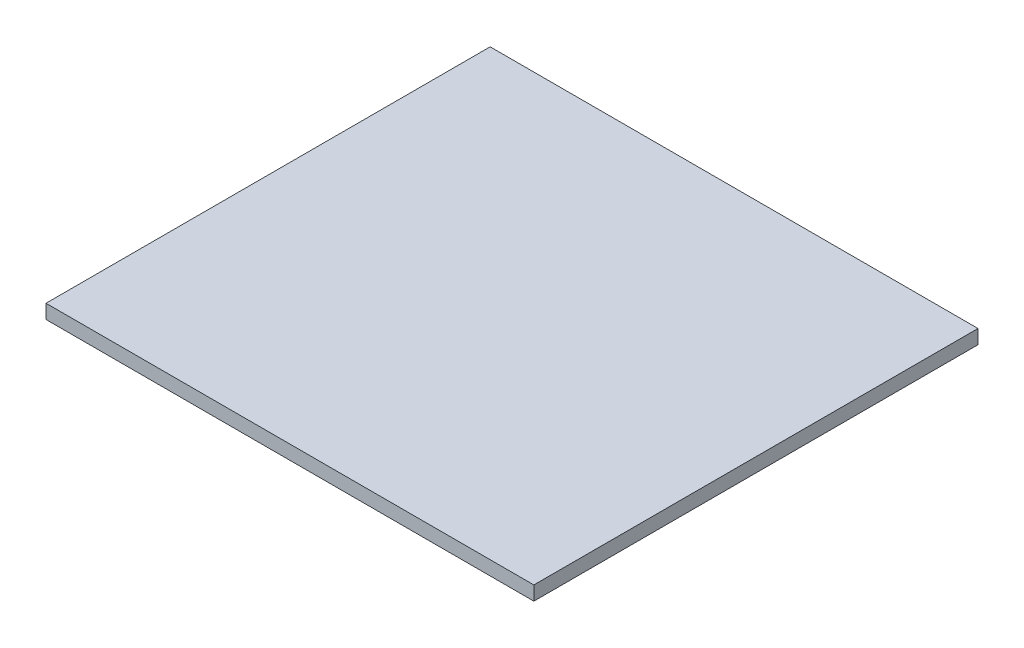
SolidWorks part; units mm, degrees
ref_plane "Front" through (0, 0, 0) normal (0, 0, 1) x (1, 0, 0)
ref_plane "Top" through (0, 0, 0) normal (0, 1, 0) x (1, 0, 0)
ref_plane "Right" through (0, 0, 0) normal (1, 0, 0) x (0, 0, -1)
sketch "草图1" plane through (0, 0, 0) normal (0, 1, 0) x (1, 0, 0)
  line L1 (0, 0) -> (346, 0)
  line L2 (0, 0) -> (0, 315)
  line L3 (0, 315) -> (346, 315)
  line L4 (346, 0) -> (346, 315)
  dimension "D1" = 346
  dimension "D2" = 315
extrude "凸台-拉伸1" add sketch "草图1" along normal blind 10
